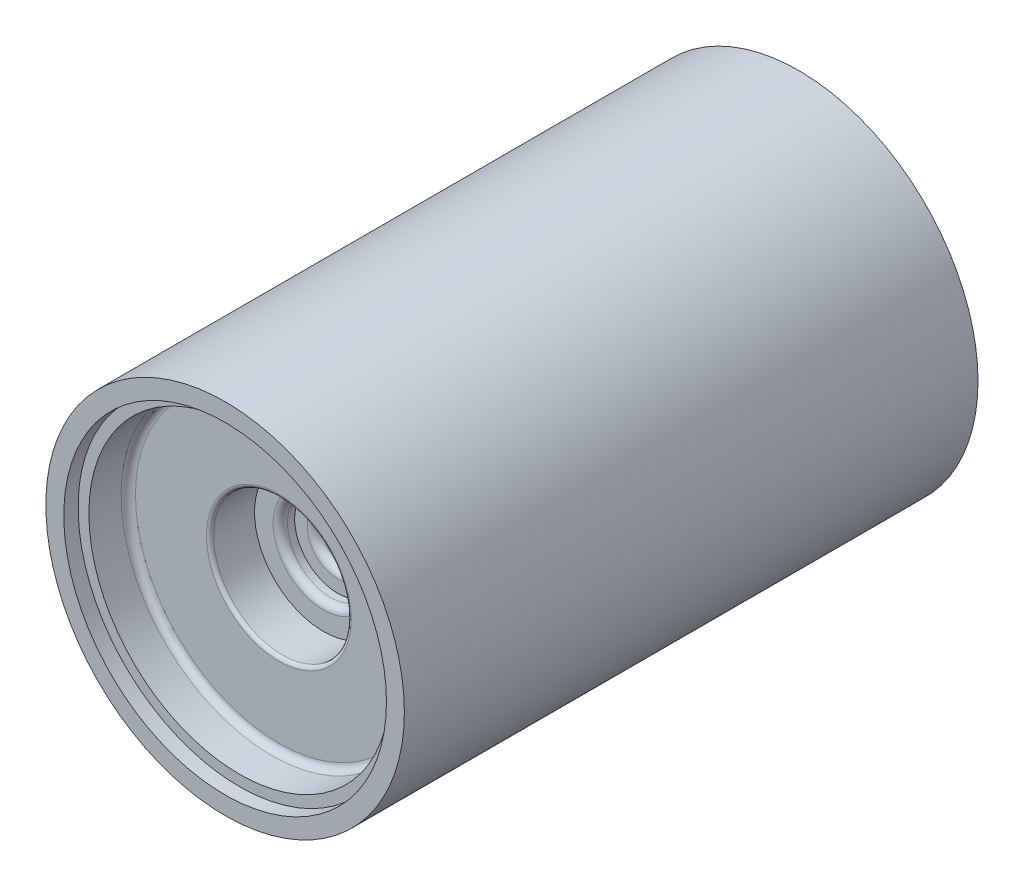
SolidWorks part; units mm, degrees
ref_plane "Plano frontal" through (0, 0, 0) normal (0, 0, 1) x (1, 0, 0)
ref_plane "Plano superior" through (0, 0, 0) normal (0, 1, 0) x (1, 0, 0)
ref_plane "Plano direito" through (0, 0, 0) normal (1, 0, 0) x (0, 0, -1)
sketch "Esboço1" plane through (0, 0, 0) normal (0, 0, 1) x (1, 0, 0)
  circle A0 centre (0, 0) radius 25
  circle A1 centre (0, 0) radius 3.25
  dimension "D1" = 50
  dimension "D2" = 6.5
extrude "Ressalto-extrusão1" add sketch "Esboço1" along normal mid plane 80
fillet "Filete2" radius 1 2 edges at (3.25, 0, 40) (3.25, 0, -40)
sketch "Esboço6" plane through (0, 0, -40) normal (0, 0, -1) x (-1, 0, 0)
  circle A0 centre (0, 0) radius 21
  circle A1 centre (0, 0) radius 25 construction
  dimension "D1" = 4
extrude "Corte-extrusão3" cut sketch "Esboço6" against normal blind 7.5
sketch "Esboço7" plane through (0, 0, 40) normal (0, 0, 1) x (1, 0, 0)
  circle A0 centre (0, 0) radius 21
  circle A1 centre (0, 0) radius 25 construction
  dimension "D1" = 4
extrude "Corte-extrusão4" cut sketch "Esboço7" against normal blind 7.5
sketch "Esboço3" plane through (0, 0, 32.5) normal (0, 0, 1) x (1, 0, 0)
  circle A0 centre (0, 0) radius 9.6
  dimension "D1" = 19.2
extrude "Corte-extrusão1" cut sketch "Esboço3" against normal blind 6.2
sketch "Esboço4" plane through (0, 0, -32.5) normal (0, 0, -1) x (-1, 0, 0)
  circle A0 centre (0, 0) radius 9.6
  dimension "D1" = 19.2
extrude "Corte-extrusão2" cut sketch "Esboço4" against normal blind 6.2
fillet "Filete3" radius 0.5 2 edges at (9.6, 0, 32.5) (-9.6, 0, -32.5)
ref_plane "Plano1" through (0, 0, 37.5) normal (0, 0, 1) x (1, 0, 0)
fillet "Filete4" radius 1 4 edges at (21, 0, 32.5) (-21, 0, -32.5) (-3.25, 0, -26.3) (3.25, 0, 26.3)
sketch "Esboço8" plane through (0, 0, 40) normal (0, 0, 1) x (1, 0, 0)
  circle A0 centre (0, 0) radius 22.5
  circle A1 centre (0, 0) radius 21 construction
  circle A2 centre (0, 0) radius 21
  dimension "D1" = 1.5
extrude "Corte-extrusão5" cut sketch "Esboço8" against normal blind 2
sketch "Esboço9" plane through (0, 0, -40) normal (0, 0, -1) x (-1, 0, 0)
  circle A0 centre (0, 0) radius 22.5
  circle A1 centre (0, 0) radius 21 construction
  circle A2 centre (0, 0) radius 21
  dimension "D1" = 1.5
extrude "Corte-extrusão6" cut sketch "Esboço9" against normal blind 2
sketch "Esboço10" plane through (0, 0, 26.3) normal (0, 0, 1) x (1, 0, 0)
  circle A0 centre (0, 0) radius 6
  dimension "D1" = 12
extrude "Corte-extrusão7" cut sketch "Esboço10" against normal blind 2
sketch "Esboço12" plane through (0, 0, -26.3) normal (0, 0, -1) x (-1, 0, 0)
  circle A0 centre (0, 0) radius 6 construction
  circle A1 centre (0, 0) radius 6
extrude "Corte-extrusão8" cut sketch "Esboço12" against normal blind 2
fillet "Filete5" radius 1 4 edges at (-3.25, 0, -24.3) (3.25, 0, 24.3) (6, 0, 26.3) (-6, 0, -26.3)
